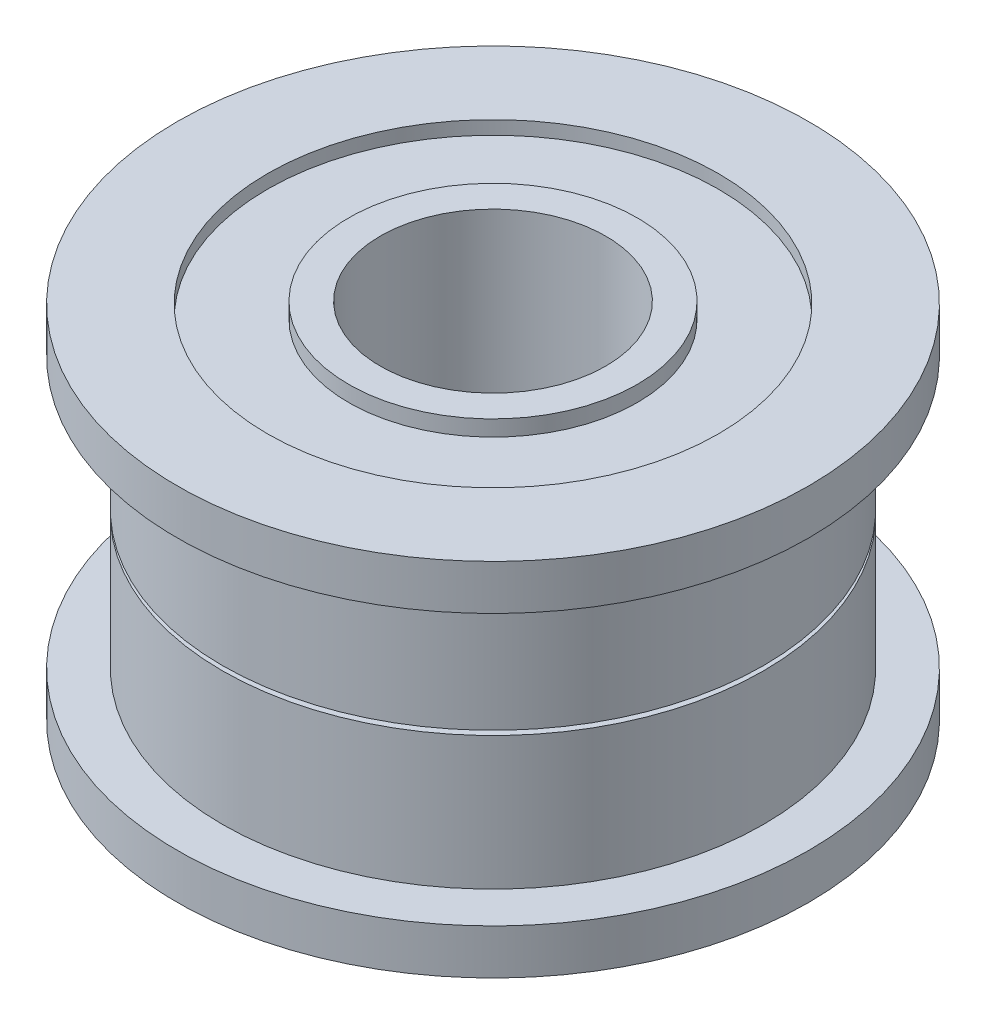
SolidWorks part; units mm, degrees
ref_plane "前视基准面" through (0, 0, 0) normal (0, 0, 1) x (1, 0, 0)
ref_plane "上视基准面" through (0, 0, 0) normal (0, 1, 0) x (1, 0, 0)
ref_plane "右视基准面" through (0, 0, 0) normal (1, 0, 0) x (0, 0, -1)
sketch "草图1" plane through (0, 0, 0) normal (0, 0, 1) x (1, 0, 0)
  line L0 (2.5, 0) -> (3.2, 0)
  line L1 (7, 0) -> (7, 1)
  line L2 (7, 1) -> (6, 1)
  line L3 (6, 1) -> (6, 4) construction
  line L4 (6, 4) -> (5, 4) construction
  line L5 (3.2, 4) -> (2.5, 4)
  line L6 (3.2, 4) -> (3.2, 3.7)
  line L7 (3.2, 3.7) -> (5, 3.7)
  line L8 (5, 3.7) -> (5, 4) construction
  line L9 (3.2, 0) -> (3.2, 0.3)
  line L10 (3.2, 0.3) -> (5, 0.3)
  line L11 (5, 0.3) -> (5, 0)
  line L12 (2.5, 4) -> (2.5, 0)
  line L13 (5, 0) -> (7, 0)
  line L14 (0, -1000) -> (0, 49000) construction
  line L15 (2.5, 4) -> (2.5, 4.05)
  line L16 (2.5, 4.05) -> (3.2, 4.05)
  line L17 (3.2, 4.05) -> (3.2, 4)
  line L18 (2.5, 0) -> (2.5, -0.05)
  line L19 (2.5, -0.05) -> (3.2, -0.05)
  line L20 (3.2, -0.05) -> (3.2, 0)
  line L21 (3.2, 0) -> (3.2014, -0.0046)
  line L22 (6, 1) -> (6, 3.95)
  line L23 (6, 3.95) -> (5, 3.95)
  line L24 (5, 3.95) -> (5, 3.7)
  dimension "D1" = 2.5
  dimension "D2" = 3.2
  dimension "D3" = 7
  dimension "D4" = 6
  dimension "D5" = 0.3
  dimension "D6" = 0.3
  dimension "D7" = 4
  dimension "D8" = 1
  dimension "D9" = 1
  dimension "D10" = 0.05
  dimension "D11" = 0.05
  dimension "D12" = 0.05
revolve "旋转1" add sketch "草图1" angle 360 about L14
ref_plane "基准面1" through (0, 4, 0) normal (0, 1, 0) x (1, 0, 0)
mirror "镜向1" about plane through (0, 4, 0) normal (0, 1, 0) of "旋转1"
